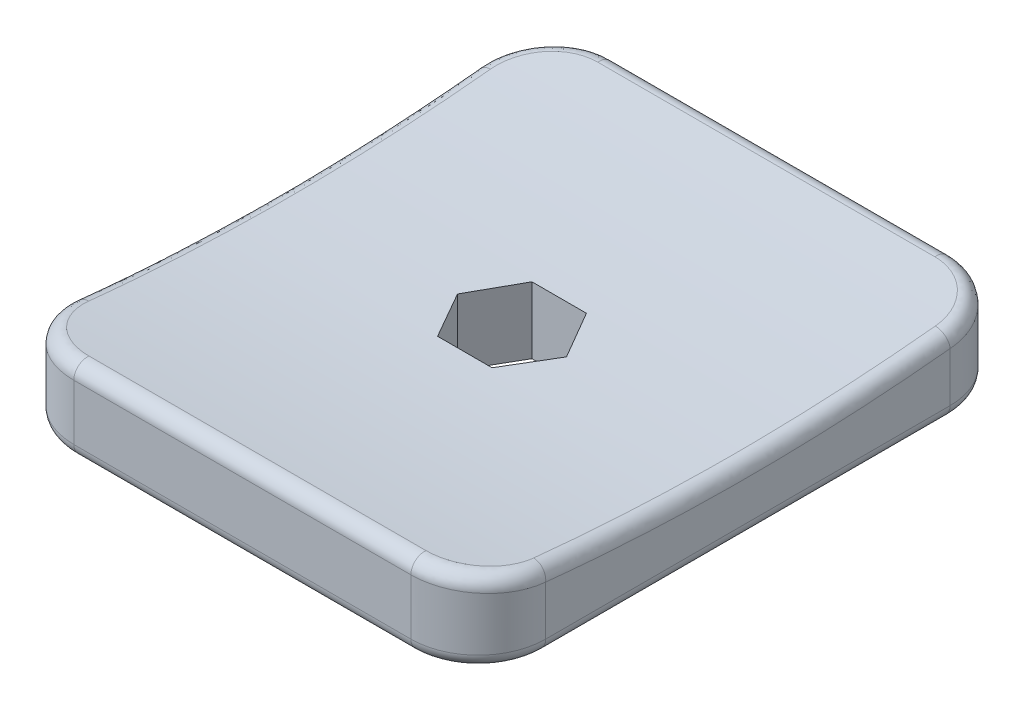
SolidWorks part; units mm, degrees
material "ABS"
ref_plane "Front Plane" through (0, 0, 0) normal (0, 0, 1) x (1, 0, 0)
ref_plane "Top Plane" through (0, 0, 0) normal (0, 1, 0) x (1, 0, 0)
ref_plane "Right Plane" through (0, 0, 0) normal (1, 0, 0) x (0, 0, -1)
sketch "Sketch1" plane through (0, 0, 0) normal (0, 1, 0) x (1, 0, 0)
  line L1 (12.5, -20) -> (-12.5, -20)
  line L2 (17.5, -15) -> (17.5, 15)
  line L3 (12.5, 20) -> (-12.5, 20)
  line L4 (-17.5, -15) -> (-17.5, 15)
  line L5 (17.5, -20) -> (-17.5, 20) construction
  line L6 (17.5, 20) -> (-17.5, -20) construction
  line L7 (4.0415, 0) -> (2.0207, 3.5)
  line L8 (2.0207, 3.5) -> (-2.0207, 3.5)
  line L9 (-2.0207, 3.5) -> (-4.0415, 0)
  line L10 (-4.0415, 0) -> (-2.0207, -3.5)
  line L11 (-2.0207, -3.5) -> (2.0207, -3.5)
  line L12 (2.0207, -3.5) -> (4.0415, 0)
  circle A0 centre (0, 0) radius 3.5 construction
  arc A1 (12.5, 20) -> (17.5, 15) centre (12.5, 15) cw
  arc A2 (12.5, -20) -> (17.5, -15) centre (12.5, -15) ccw
  arc A3 (-12.5, -20) -> (-17.5, -15) centre (-12.5, -15) cw
  arc A4 (-17.5, 15) -> (-12.5, 20) centre (-12.5, 15) cw
  point P0 (0, 0)
  dimension "D3" = 20
  dimension "D1" = 7
  dimension "D4" = 5
  dimension "D2" = 17.5
extrude "Boss-Extrude1" add sketch "Sketch1" against normal blind 6.27
sketch "Sketch5" plane through (17.5, 0, 0) normal (1, 0, 0) x (0, 0, -1)
  line L0 (-20, 0) -> (20, 0)
  line L1 (-15, -6.27) -> (15, -6.27) construction
  spline S0 degree 2 poles (-20, 0) (0, -2.74) (20, 0) knots 0 0 0 1 1 1
  dimension "D1" = 15
  dimension "D2" = 4.9
extrude "Cut-Extrude2" cut sketch "Sketch5" against normal through all
fillet "Fillet1" radius 1 16 edges at (0, -6.27, 20) (-16.0355, -6.27, 18.5355) (-17.5, -6.27, 0) (-16.0355, -6.27, -18.5355) (0, -6.27, -20) (16.0355, -6.27, -18.5355) (17.5, -6.27, 0) (0, 0, 20) (-16.3925, -0.2432, 18.1382) (-15.6031, -0.1439, -18.9205) (0, 0, -20) (16.3925, -0.2432, -18.1382) (16.0355, -6.27, 18.5355) (15.6031, -0.1439, 18.9205)
sketch "Sketch3" plane through (0, -6.27, 0) normal (0, -1, 0) x (1, 0, 0)
  circle A0 centre (0, 0) radius 7.0821
